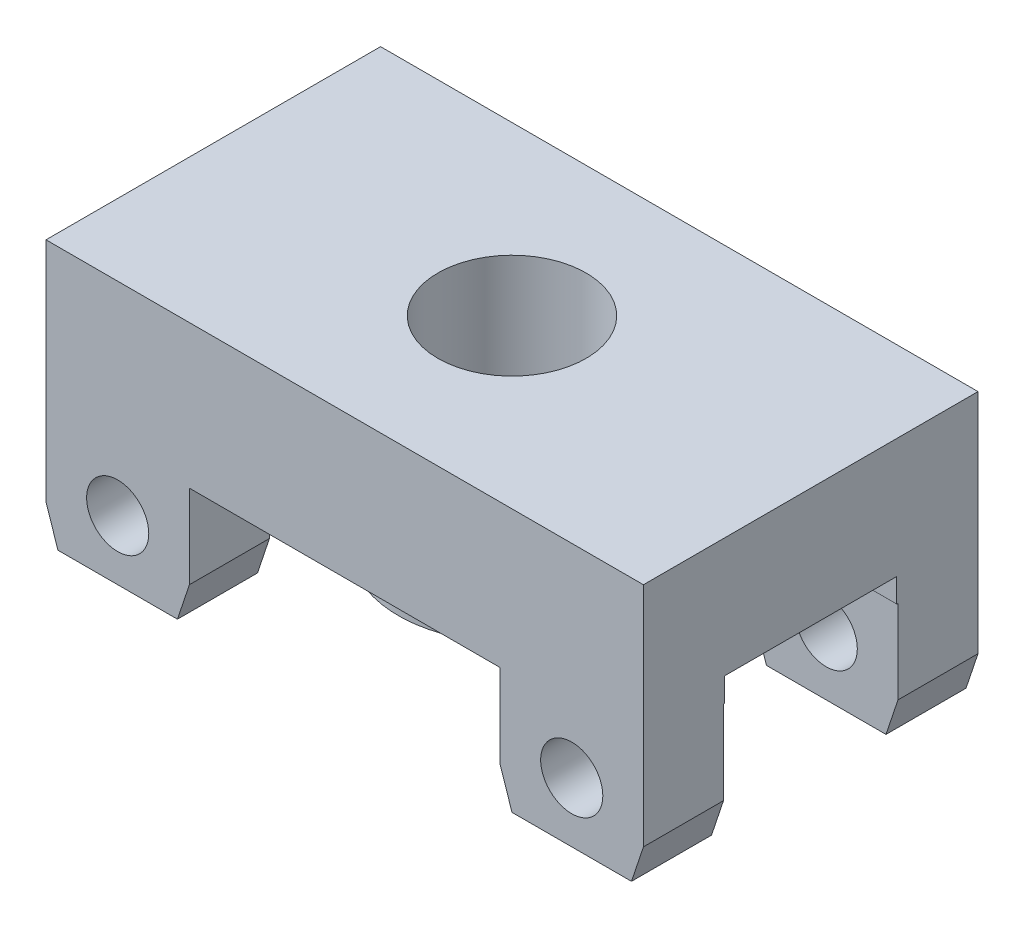
SolidWorks part; units mm, degrees
ref_plane "前视基准面" through (0, 0, 0) normal (0, 0, 1) x (1, 0, 0)
ref_plane "上视基准面" through (0, 0, 0) normal (0, 1, 0) x (1, 0, 0)
ref_plane "右视基准面" through (0, 0, 0) normal (1, 0, 0) x (0, 0, -1)
other "Configuration Table"
sketch "草图1" plane through (0, 0, 0) normal (0, 0, 1) x (1, 0, 0)
  line L0 (0, 0) -> (50, 0)
  line L1 (50, 0) -> (50, 12)
  line L2 (50, 12) -> (0, 12)
  line L3 (0, 12) -> (0, 0)
  dimension "width" = 50
  dimension "height" = 12
extrude "Upper_crossbar" add sketch "草图1" along normal blind 28
sketch "草图2" plane through (0, 0, 0) normal (0, -1, 0) x (1, 0, 0)
  circle A0 centre (25, 14) radius 9.5
  dimension "diameter" = 19
  dimension "x" = 25
  dimension "y" = 14
extrude "Lower_guide_sleeve" add sketch "草图2" along normal blind 5
sketch "草图3" plane through (0, 12, 0) normal (0, 1, 0) x (1, 0, 0)
  circle A0 centre (25, -14) radius 6.2
  dimension "diameter" = 12.4
  dimension "x" = 25
  dimension "y" = 14
extrude "Spindle_through_bore" cut sketch "草图3" against normal through all
ref_plane "Hinge_ear_plane" through (0, 0, 21.3) normal (0, 0, 1) x (1, 0, 0)
sketch "草图5" plane through (0, 0, 21.3) normal (0, 0, 1) x (1, 0, 0)
  line L0 (1, -10) -> (11, -10)
  line L1 (11, -10) -> (12, -7)
  line L2 (12, -7) -> (12, 1)
  line L3 (12, 1) -> (0, 1)
  line L4 (0, 1) -> (0, -7)
  line L5 (0, -7) -> (1, -10)
  dimension "x0" = 1
  dimension "x1" = 11
  dimension "x2" = 12
  dimension "y0" = 10
  dimension "y2" = 7
  dimension "y3" = 1
  dimension "y5" = 7
extrude "Upper_hinge_ear" add sketch "草图5" along normal blind 6.7
sketch "草图6" plane through (0, 0, 28) normal (0, 0, 1) x (1, 0, 0)
  circle A0 centre (6, -5) radius 2.6
  dimension "diameter" = 5.2
  dimension "x" = 6
  dimension "y" = 5
extrude "Upper_hinge_bore" cut sketch "草图6" against normal through all
sketch "草图7" plane through (0, 0, 21.3) normal (0, 0, 1) x (1, 0, 0)
  line L0 (39, -10) -> (49, -10)
  line L1 (49, -10) -> (50, -7)
  line L2 (50, -7) -> (50, 1)
  line L3 (50, 1) -> (38, 1)
  line L4 (38, 1) -> (38, -7)
  line L5 (38, -7) -> (39, -10)
  dimension "x0" = 39
  dimension "x1" = 49
  dimension "x2" = 50
  dimension "x4" = 38
  dimension "y0" = 10
  dimension "y2" = 7
  dimension "y3" = 1
  dimension "y5" = 7
extrude "凸台-拉伸2" add sketch "草图7" along normal blind 6.7
sketch "草图8" plane through (0, 0, 28) normal (0, 0, 1) x (1, 0, 0)
  circle A0 centre (44, -5) radius 2.6
  dimension "diameter" = 5.2
  dimension "x" = 44
  dimension "y" = 5
extrude "切除-拉伸2" cut sketch "草图8" against normal through all
sketch "草图9" plane through (0, 0, 0) normal (0, 0, 1) x (1, 0, 0)
  line L0 (1, -10) -> (11, -10)
  line L1 (11, -10) -> (12, -7)
  line L2 (12, -7) -> (12, 1)
  line L3 (12, 1) -> (0, 1)
  line L4 (0, 1) -> (0, -7)
  line L5 (0, -7) -> (1, -10)
  dimension "x0" = 1
  dimension "x1" = 11
  dimension "x2" = 12
  dimension "y0" = 10
  dimension "y2" = 7
  dimension "y3" = 1
  dimension "y5" = 7
extrude "Opposite_hinge_ear" add sketch "草图9" along normal blind 6.7
sketch "草图10" plane through (0, 0, 0) normal (0, 0, -1) x (-1, 0, 0)
  circle A0 centre (-6, -5) radius 2.6
  dimension "diameter" = 5.2
  dimension "x" = 6
  dimension "y" = 5
extrude "Opposite_hinge_bore" cut sketch "草图10" against normal through all
sketch "草图11" plane through (0, 0, 0) normal (0, 0, 1) x (1, 0, 0)
  line L0 (39, -10) -> (49, -10)
  line L1 (49, -10) -> (50, -7)
  line L2 (50, -7) -> (50, 1)
  line L3 (50, 1) -> (38, 1)
  line L4 (38, 1) -> (38, -7)
  line L5 (38, -7) -> (39, -10)
  dimension "x0" = 39
  dimension "x1" = 49
  dimension "x2" = 50
  dimension "x4" = 38
  dimension "y0" = 10
  dimension "y2" = 7
  dimension "y3" = 1
  dimension "y5" = 7
extrude "凸台-拉伸4" add sketch "草图11" along normal blind 6.7
sketch "草图12" plane through (0, 0, 0) normal (0, 0, -1) x (-1, 0, 0)
  circle A0 centre (-44, -5) radius 2.6
  dimension "diameter" = 5.2
  dimension "x" = 44
  dimension "y" = 5
extrude "切除-拉伸4" cut sketch "草图12" against normal through all
ref_plane "Arm_clearance_midplane" through (0, 0, 14) normal (0, 0, 1) x (1, 0, 0)
sketch "草图14" plane through (0, 0, 14) normal (0, 0, 1) x (1, 0, 0)
  line L0 (-2, -0.2) -> (18, -0.2)
  line L1 (18, -0.2) -> (18, 2)
  line L2 (18, 2) -> (-2, 2)
  line L3 (-2, 2) -> (-2, -0.2)
  dimension "x0" = 2
  dimension "x1" = 18
  dimension "y0" = 0.2
  dimension "y2" = 2
extrude "Arm_swing_clearance" cut sketch "草图14" against normal mid plane 14.4
sketch "草图15" plane through (0, 0, 14) normal (0, 0, 1) x (1, 0, 0)
  line L0 (32, -0.2) -> (52, -0.2)
  line L1 (52, -0.2) -> (52, 2)
  line L2 (52, 2) -> (32, 2)
  line L3 (32, 2) -> (32, -0.2)
  dimension "x0" = 32
  dimension "x1" = 52
  dimension "y0" = 0.2
  dimension "y2" = 2
extrude "切除-拉伸6" cut sketch "草图15" against normal mid plane 14.4
